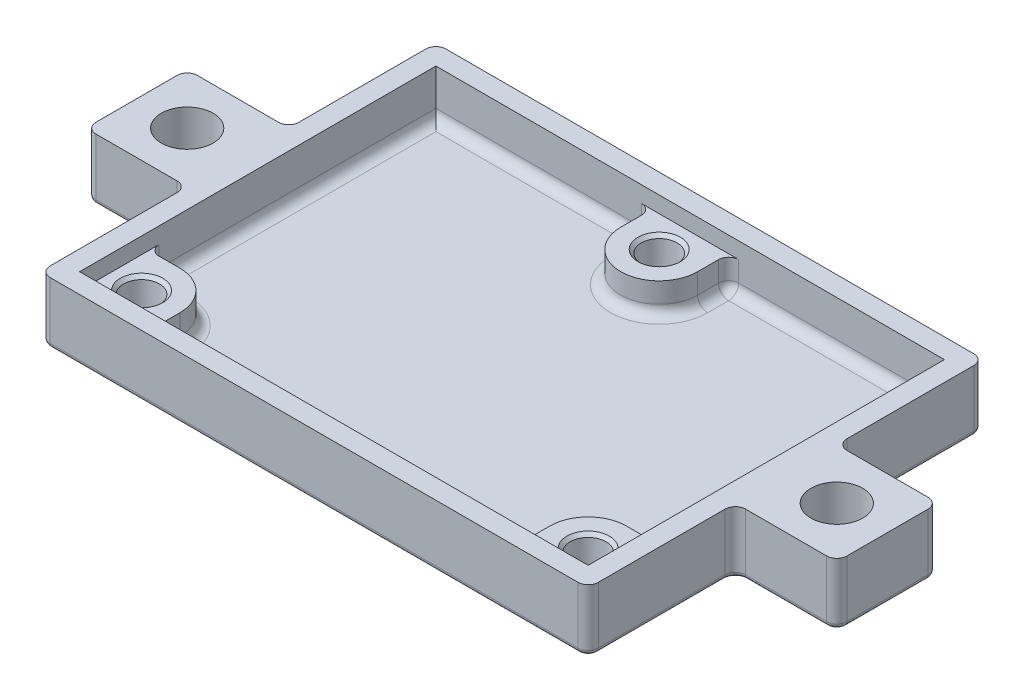
SolidWorks part; units mm, degrees
ref_plane "Front Plane" through (0, 0, 0) normal (0, 0, 1) x (1, 0, 0)
ref_plane "Top Plane" through (0, 0, 0) normal (0, 1, 0) x (1, 0, 0)
ref_plane "Right Plane" through (0, 0, 0) normal (1, 0, 0) x (0, 0, -1)
sketch "Sketch1" plane through (0, 0, 0) normal (0, 1, 0) x (1, 0, 0)
  line L0 (-41.1458, 0) -> (37.3326, 0) construction
  line L1 (-27, -19.5) -> (27, -19.5)
  line L2 (-27, -19.5) -> (-27, 19.5)
  line L3 (-27, 19.5) -> (27, 19.5)
  line L4 (27, -19.5) -> (27, 19.5)
  line L5 (-27, -19.5) -> (27, 19.5) construction
  line L6 (-27, 19.5) -> (27, -19.5) construction
  line L7 (0, 33.589) -> (0, -25.3286) construction
  line L8 (-37, -5) -> (-27, -5)
  line L9 (-37, -5) -> (-37, 5)
  line L10 (-37, 5) -> (-27, 5)
  line L11 (-27, -5) -> (-27, 5)
  line L12 (-37, -5) -> (-27, 5) construction
  line L13 (-37, 5) -> (-27, -5) construction
  line L14 (37, -5) -> (37, 5)
  line L15 (37, 5) -> (27, 5)
  line L16 (37, -5) -> (27, -5)
  circle A0 centre (-32, 0) radius 2.5527
  circle A1 centre (32, 0) radius 2.5527
  point P0 (0, 0)
  point P8 (-32, 0)
  point P23 (0, 0)
  dimension "D5" = 5.1054
  dimension "D1" = 54
  dimension "D2" = 39
  dimension "D3" = 10
  dimension "D4" = 10
extrude "Boss-Extrude1" add sketch "Sketch1" along normal blind 6.1 contours L1 L4 L3 L2 | L16 L14 L15 L4 A1 | L10 L9 L8 L2 A0
sketch "Sketch2" plane through (0, 6.1, 0) normal (0, 1, 0) x (1, 0, 0)
  line L0 (0, 27.4) -> (0, -30.8783) construction
  line L1 (-42.9811, 0) -> (41.0645, 0) construction
  line L3 (-25.05, -17.55) -> (25.05, -17.55)
  line L4 (-25.05, -17.55) -> (-25.05, 17.55)
  line L5 (-25.05, 17.55) -> (25.05, 17.55)
  line L6 (25.05, -17.55) -> (25.05, 17.55)
  line L7 (-25.05, -17.55) -> (25.05, 17.55) construction
  line L8 (-25.05, 17.55) -> (25.05, -17.55) construction
  point P5 (0, 0)
  dimension "D1" = 50.1
  dimension "D2" = 35.1
extrude "Cut-Extrude1" cut sketch "Sketch2" against normal blind 1.6
sketch "Sketch3" plane through (0, 4.5, 0) normal (0, 1, 0) x (1, 0, 0)
  line L0 (0, 25.6254) -> (0, -24.9156) construction
  line L1 (-43.478, 0) -> (41.2775, 0) construction
  line L2 (-5.4043, 14.5) -> (7.1001, 14.5) construction
  line L3 (-3.79, 14.5) -> (-3.79, 17.55)
  line L4 (25.05, 17.55) -> (-25.05, 17.55) construction
  line L5 (3.79, 14.5) -> (3.79, 17.55)
  line L7 (-22, -6.9215) -> (-22, -24.9156) construction
  line L8 (-15.6235, -14.5) -> (-28.7086, -14.5) construction
  line L9 (-18.21, -14.5) -> (-18.21, -17.55)
  line L10 (-25.05, -17.55) -> (25.05, -17.55) construction
  line L11 (-22, -10.71) -> (-25.05, -10.71)
  line L12 (-25.05, 17.55) -> (-25.05, -17.55) construction
  line L13 (-18.21, -17.55) -> (18.21, -17.55)
  line L14 (-25.05, -10.71) -> (-25.05, 17.55)
  line L15 (-25.05, 17.55) -> (-3.79, 17.55)
  line L16 (18.21, -14.5) -> (18.21, -17.55)
  line L17 (22, -10.71) -> (25.05, -10.71)
  line L18 (25.05, -10.71) -> (25.05, 17.55)
  line L19 (25.05, 17.55) -> (3.79, 17.55)
  arc A0 (-3.79, 14.5) -> (3.79, 14.5) centre (0, 14.5) ccw
  arc A1 (-18.21, -14.5) -> (-22, -10.71) centre (-22, -14.5) ccw
  arc A2 (18.21, -14.5) -> (22, -10.71) centre (22, -14.5) cw
  point P31 (0, -17.55)
  dimension "D1" = 7.58
  dimension "D3" = 7.58
  dimension "D2" = 14.5
  dimension "D4" = 22
  dimension "D5" = 14.5
extrude "Cut-Extrude2" cut sketch "Sketch3" against normal blind 3
sketch "Sketch4" plane through (0, 4.5, 0) normal (0, 1, 0) x (1, 0, 0)
  line L0 (0, 26.0262) -> (0, -25.2956) construction
  line L1 (-42.2713, 0) -> (43.691, 0) construction
  circle A0 centre (0, 14.5) radius 1.56
  circle A1 centre (-22, -14.5) radius 1.56
  circle A2 centre (22, -14.5) radius 1.56
  dimension "D1" = 3.12
  dimension "D2" = 14.5
  dimension "D3" = 22
  dimension "D4" = 14.5
extrude "Cut-Extrude3" cut sketch "Sketch4" against normal through all
sketch "Sketch5" plane through (0, 4.5, 0) normal (0, 1, 0) x (1, 0, 0)
  line L0 (0, 25.6254) -> (0, -24.7736) construction
  line L1 (-41.9164, 0) -> (40.1417, 0) construction
  circle A0 centre (0, 14.5) radius 1.79
  circle A1 centre (-22, -14.5) radius 1.79
  circle A2 centre (22, -14.5) radius 1.79
  dimension "D1" = 3.58
extrude "Cut-Extrude4" cut sketch "Sketch5" against normal blind 2.92
draft "Draft2" type of draft neutral plane draft angle 4 faces to draft 1 face at (0, 1.58, -12.71) neutral plane through (0, 4.5, 0) neutral plane normal (0, 1, 0) parameters "D1"=4
draft "Draft3" type of draft neutral plane draft angle 4 faces to draft 1 face at (-22, 1.58, 16.29) neutral plane through (0, 4.5, 0) neutral plane normal (0, 1, 0) parameters "D1"=4
draft "Draft4" type of draft neutral plane draft angle 4 faces to draft 1 face at (22, 1.58, 12.71) neutral plane through (0, 4.5, 0) neutral plane normal (0, 1, 0) parameters "D1"=4
fillet "Fillet1" radius 1 12 edges at (-37, 3.05, -5) (-27, 3.05, -5) (-27, 3.05, -19.5) (27, 3.05, -19.5) (27, 3.05, -5) (37, 3.05, -5) (37, 3.05, 5) (27, 3.05, 5) (27, 3.05, 19.5) (-27, 3.05, 19.5) (-27, 3.05, 5) (-37, 3.05, 5)
fillet "Fillet2" radius 1 20 edges at (3.79, 1.5, -16.025) (14.42, 1.5, -17.55) (25.05, 1.5, -3.42) (23.525, 1.5, 10.71) (19.3201, 1.5, 11.8201) (18.21, 1.5, 16.025) (0, 1.5, 17.55) (-18.21, 1.5, 16.025) (-19.3201, 1.5, 11.8201) (-23.525, 1.5, 10.71) (-25.05, 1.5, -3.42) (-14.42, 1.5, -17.55) (-3.79, 1.5, -16.025) (0, 1.5, -10.71) (3.79, 3, -17.55) (-3.79, 3, -17.55) (25.05, 3, 10.71) (18.21, 3, 17.55) (-18.21, 3, 17.55) (-25.05, 3, 10.71)
fillet "Fillet3" radius 0.5 24 edges at (-27.2929, 0, -5.2929) (-32, 0, -5) (-36.7071, 0, -4.7071) (-37, 0, 0) (-36.7071, 0, 4.7071) (-32, 0, 5) (-27.2929, 0, 5.2929) (-27, 0, 12.25) (-26.7071, 0, 19.2071) (0, 0, 19.5) (26.7071, 0, 19.2071) (27, 0, 12.25) (27.2929, 0, 5.2929) (32, 0, 5) (36.7071, 0, 4.7071) (37, 0, 0) (36.7071, 0, -4.7071) (32, 0, -5) (27.2929, 0, -5.2929) (27, 0, -12.25) (26.7071, 0, -19.2071) (0, 0, -19.5) (-26.7071, 0, -19.2071) (-27, 0, -12.25)
chamfer "Chamfer1" distance 0.3 angle 45 3 edges at (22, 4.5, 12.71) (-22, 4.5, 16.29) (0, 4.5, -12.71)
